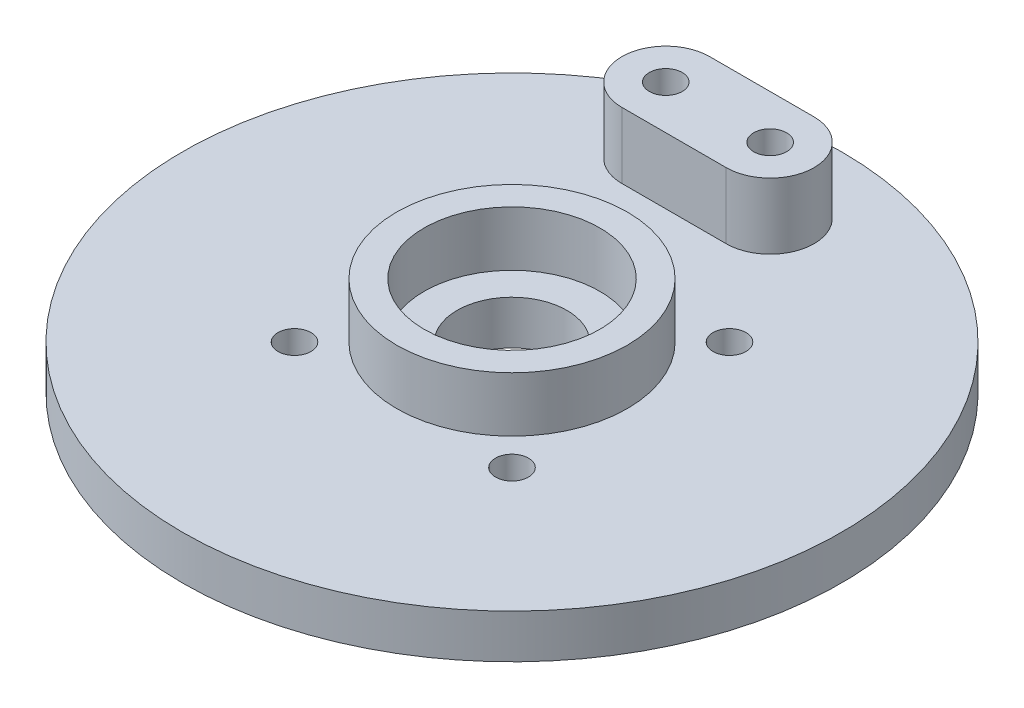
SolidWorks part; units mm, degrees
ref_plane "Front" through (0, 0, 0) normal (0, 0, 1) x (1, 0, 0)
ref_plane "Top" through (0, 0, 0) normal (0, 1, 0) x (1, 0, 0)
ref_plane "Right" through (0, 0, 0) normal (1, 0, 0) x (0, 0, -1)
sketch "Sketch1" plane through (0, 0, 0) normal (0, 1, 0) x (1, 0, 0)
  circle A0 centre (0, 0) radius 30
  circle A1 centre (0, 0) radius 5
  dimension "D1" = 60
  dimension "D2" = 10
extrude "Boss-Extrude1" add sketch "Sketch1" along normal blind 4
sketch "Sketch4" plane through (0, 4, 0) normal (0, 1, 0) x (1, 0, 0)
  circle A0 centre (0, 0) radius 8
  circle A1 centre (0, 0) radius 10.5
  dimension "D1" = 16
  dimension "D2" = 2.5
extrude "Boss-Extrude2" add sketch "Sketch4" along normal blind 5
sketch "Sketch5" plane through (0, 4, 0) normal (0, 1, 0) x (1, 0, 0)
  line L7 (14.5977, 15.4464) -> (14.5977, 4.9464)
  line L8 (-5.4023, 25.4464) -> (14.5977, 25.4464)
  line L9 (-5.4023, 25.4464) -> (-5.4023, 15.4464)
  line L10 (-5.4023, 15.4464) -> (14.5977, 15.4464)
  line L11 (14.5977, 25.4464) -> (14.5977, 15.4464)
  line L12 (-5.4023, 25.4464) -> (14.5977, 15.4464) construction
  line L13 (-5.4023, 15.4464) -> (14.5977, 25.4464) construction
  line L14 (14.09, 7.0565) -> (-3.9023, 15.4464)
  circle A1 centre (14.09, 7.0565) radius 2.1703
  point P16 (4.5977, 20.4464)
  dimension "D7" = 1.5
  dimension "D4" = 10
  dimension "D5" = 20
  dimension "D6" = 10.5
  dimension "D8" = 25
sketch "Sketch6" plane through (0, 4, 0) normal (0, 1, 0) x (1, 0, 0)
  line L0 (0, 0) -> (0, 30) construction
  line L1 (0, 0) -> (-30, 0) construction
  circle A0 centre (-7.5, 21.5) radius 1.5
  circle A1 centre (2, 21.5) radius 1.5
  circle A2 centre (0, 0) radius 30 construction
  point P10 (0, 0)
  dimension "D1" = 3
  dimension "D2" = 3
  dimension "D3" = 9.5
  dimension "D4" = 7.5
  dimension "D5" = 21.5
extrude "Cut-Extrude3" cut sketch "Sketch6" against normal through all
sketch "Sketch7" plane through (0, 4, 0) normal (0, 1, 0) x (1, 0, 0)
  line L0 (2, 25.5) -> (-7.5, 25.5)
  line L1 (-7.5, 17.5) -> (2, 17.5)
  circle A0 centre (-7.5, 21.5) radius 1.5 construction
  circle A2 centre (-7.5, 21.5) radius 1.5
  circle A3 centre (2, 21.5) radius 1.5
  arc A4 (2, 17.5) -> (2, 25.5) centre (2, 21.5) ccw
  arc A5 (-7.5, 25.5) -> (-7.5, 17.5) centre (-7.5, 21.5) ccw
  circle A6 centre (2, 21.5) radius 4 construction
  circle A7 centre (-7.5, 21.5) radius 4 construction
  point P3 (0, 0)
  dimension "D2" = 4
  dimension "D1" = 9.5
extrude "Boss-Extrude3" add sketch "Sketch7" along normal blind 6
sketch "Sketch8" plane through (0, 4, 0) normal (0, 1, 0) x (1, 0, 0)
  line L0 (0, 0) -> (-9.8995, 9.8995) construction
  line L1 (0, 0) -> (-10.5, 0) construction
  circle A0 centre (-9.8995, 9.8995) radius 1.5
  circle A1 centre (0, 0) radius 10.5 construction
  circle A2 centre (0, 0) radius 10.5 construction
  circle A3 centre (9.8995, 9.8995) radius 1.5
  circle A4 centre (9.8995, -9.8995) radius 1.5
  circle A5 centre (-9.8995, -9.8995) radius 1.5
  point P18 (0, 0)
  dimension "D2" = 3
  dimension "D1" = 14
  dimension "D3" = 45
  dimension "D4" = 4
extrude "Cut-Extrude4" cut sketch "Sketch8" against normal through all
